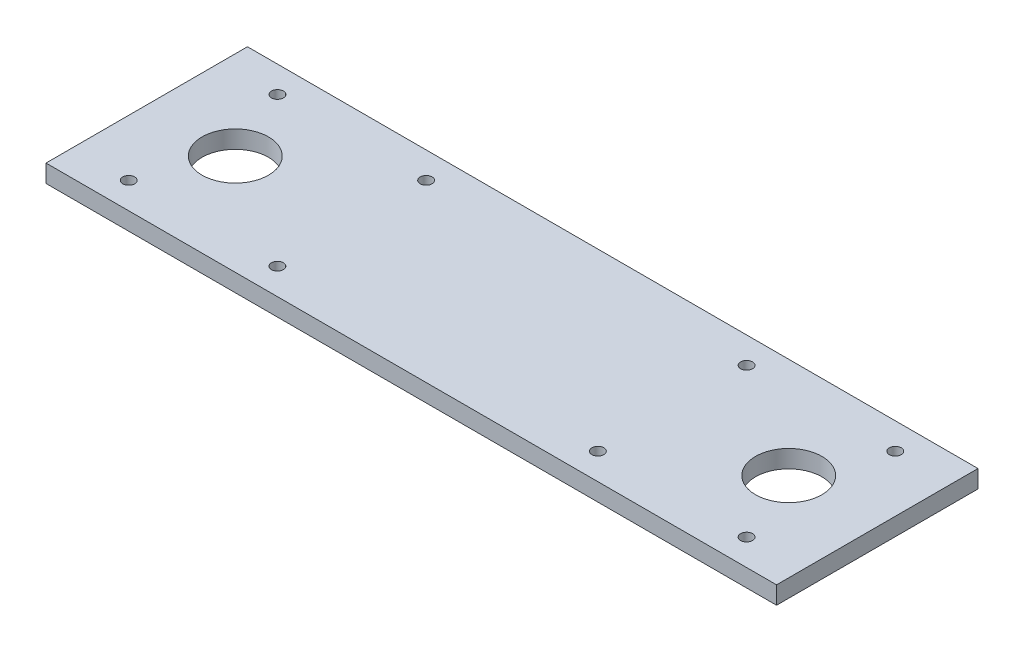
SolidWorks part; units mm, degrees
ref_plane "Front Plane" through (0, 0, 0) normal (0, 0, 1) x (1, 0, 0)
ref_plane "Top Plane" through (0, 0, 0) normal (0, 1, 0) x (1, 0, 0)
ref_plane "Right Plane" through (0, 0, 0) normal (1, 0, 0) x (0, 0, -1)
sketch "Sketch1" plane through (0, 0, 0) normal (0, 1, 0) x (1, 0, 0)
  line L1 (-165, -45.5) -> (165, -45.5)
  line L2 (-165, -45.5) -> (-165, 45.5)
  line L3 (-165, 45.5) -> (165, 45.5)
  line L4 (165, -45.5) -> (165, 45.5)
  line L5 (-165, -45.5) -> (165, 45.5) construction
  line L6 (-165, 45.5) -> (165, -45.5) construction
  point P0 (0, 0)
  dimension "D1" = 330
  dimension "D2" = 91
extrude "Boss-Extrude2" add sketch "Sketch1" along normal blind 8
sketch "Sketch4" plane through (0, 8, 0) normal (0, 1, 0) x (1, 0, 0)
  line L0 (-165, 45.5) -> (-165, -45.5) construction
  line L1 (165, 45.5) -> (-165, 45.5) construction
  line L2 (0, 45.5) -> (0, -45.5) construction
  line L3 (-165, -45.5) -> (165, -45.5) construction
  circle A0 centre (125, 0) radius 15
  circle A1 centre (-125, 0) radius 15
  circle A3 centre (-139.55, 33.59) radius 2.7
  circle A4 centre (-139.55, -33.59) radius 2.7
  circle A5 centre (-72.37, -33.59) radius 2.7
  circle A6 centre (-72.37, 33.59) radius 2.7
  circle A11 centre (139.55, -33.59) radius 2.7
  circle A12 centre (72.37, -33.59) radius 2.7
  circle A13 centre (72.37, 33.59) radius 2.7
  circle A14 centre (139.55, 33.59) radius 2.7
  dimension "D2" = 30
  dimension "D3" = 30
  dimension "D5" = 40
  dimension "D6" = 45.5
  dimension "D8" = 5.4
  dimension "D9" = 11.91
  dimension "D10" = 25.45
  dimension "D11" = 92.63
  dimension "D12" = 79.09
  dimension "D1" = 250
  dimension "D7" = 290
extrude "Cut-Extrude4" cut sketch "Sketch4" against normal blind 8
